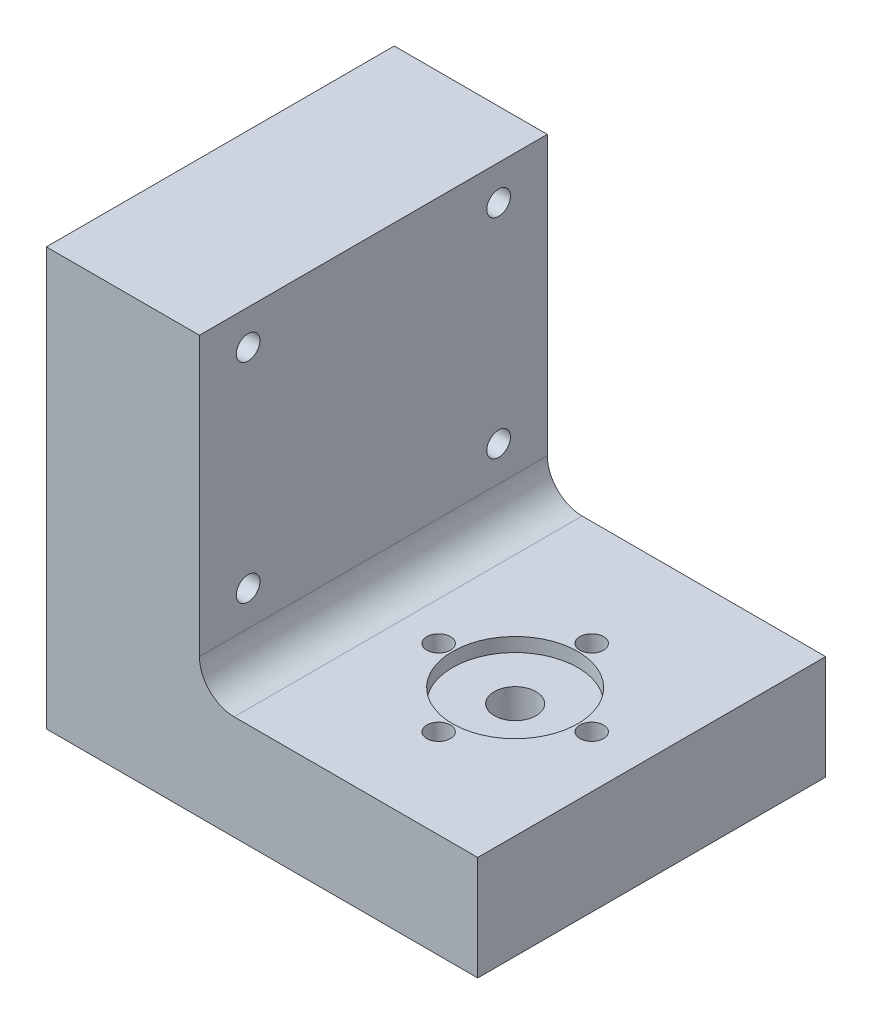
SolidWorks part; units mm, degrees
material "ABS"
ref_plane "Front Plane" through (0, 0, 0) normal (0, 0, 1) x (1, 0, 0)
ref_plane "Top Plane" through (0, 0, 0) normal (0, 1, 0) x (1, 0, 0)
ref_plane "Right Plane" through (0, 0, 0) normal (1, 0, 0) x (0, 0, -1)
sketch "Sketch1" plane through (0, 0, 0) normal (0, 0, 1) x (1, 0, 0)
  line L0 (-43.5429, 31.8) -> (-43.5429, -28.2)
  line L1 (-43.5429, -28.2) -> (18.4571, -28.2)
  line L2 (18.4571, -28.2) -> (18.4571, -13.2)
  line L3 (18.4571, -13.2) -> (-21.5429, -13.2)
  line L4 (-21.5429, -13.2) -> (-21.5429, 31.8)
  line L5 (-21.5429, 31.8) -> (-43.5429, 31.8)
  dimension "D1" = 60
  dimension "D2" = 40
  dimension "D3" = 15
  dimension "D4" = 22
extrude "Boss-Extrude1" add sketch "Sketch1" along normal blind 50
fillet "Fillet1" radius 5 1 edges at (-21.5429, -13.2, 25)
sketch "Sketch2" plane through (-21.5429, 0, 0) normal (1, 0, 0) x (0, 0, -1)
  line L0 (-50, 31.8) -> (0, 31.8) construction
  line L1 (-50, -8.2) -> (0, -8.2) construction
  line L3 (-50, -8.2) -> (-50, 31.8) construction
  line L4 (0, -8.2) -> (0, 31.8) construction
  circle A0 centre (-43, 26.8) radius 1.7
  circle A1 centre (-7, 26.8) radius 1.7
  circle A2 centre (-7, -3.2) radius 1.7
  circle A3 centre (-43, -3.2) radius 1.7
  dimension "D1" = 3.4
  dimension "D2" = 3.4
  dimension "D3" = 3.4
  dimension "D4" = 3.4
  dimension "D5" = 5
  dimension "D6" = 5
  dimension "D7" = 5
  dimension "D8" = 5
  dimension "D9" = 7
  dimension "D10" = 7
  dimension "D11" = 7
  dimension "D12" = 7
extrude "Cut-Extrude1" cut sketch "Sketch2" against normal blind 50 contours A0 | A1 | A3 | A2
sketch "Sketch3" plane through (0, -13.2, 0) normal (0, 1, 0) x (1, 0, 0)
  circle A0 centre (0, -26.1679) radius 11
  circle A1 centre (0, -26.1679) radius 3.25
  circle A2 centre (0, -26.1679) radius 9
  circle A3 centre (11, -26.1679) radius 1.7
  circle A4 centre (0, -15.1679) radius 1.7
  circle A5 centre (-11, -26.1679) radius 1.7
  circle A6 centre (0, -37.1679) radius 1.7
  dimension "D1" = 3.4
  dimension "D2" = 3.4
  dimension "D3" = 3.4
  dimension "D4" = 3.4
  dimension "D5" = 22
  dimension "D6" = 18
  dimension "D7" = 6.5
extrude "Cut-Extrude4" cut sketch "Sketch3" against normal blind 2 contours A2 A1
sketch "Sketch4" plane through (0, -13.2, 0) normal (0, 1, 0) x (1, 0, 0)
  circle A0 centre (0, -26.1679) radius 3
  dimension "D1" = 6
extrude "Cut-Extrude5" cut sketch "Sketch4" against normal blind 15
sketch "Sketch5" plane through (0, -13.2, 0) normal (0, 1, 0) x (1, 0, 0)
  circle A0 centre (0, -26.1679) radius 11
  circle A1 centre (-11, -26.1679) radius 1.7
  circle A2 centre (0, -15.1679) radius 1.7
  circle A3 centre (11, -26.1679) radius 1.7
  circle A4 centre (0, -37.1679) radius 1.7
  dimension "D1" = 22
  dimension "D2" = 3.4
  dimension "D3" = 3.4
  dimension "D4" = 3.4
  dimension "D5" = 3.4
extrude "Cut-Extrude6" cut sketch "Sketch5" against normal through all contours A2 | A1 | A4 | A3
equation "\"Bolt Circle Diameter\"= 22mm"
equation "\"h\"= 15mm"
equation "\"b\"= 50mm"
equation "\"t\"= 22mm"
equation "\"L1\"= 40mm"
equation "\"L2\"= 60mm"
equation "\"R fillet\"= 5mm"
equation "\"Shaft hole\"= 6.5mm'\""
equation "\"Bolt hole\"= 3.4mm"
equation "\"D1@Sketch1\"=\"L2\""
equation "\"D2@Sketch1\"=\"L1\""
equation "\"D3@Sketch1\"=\"h\""
equation "\"D4@Sketch1\"=\"t\""
equation "\"D1@Boss-Extrude1\"=\"b\""
equation "\"D1@Fillet1\"=\"R fillet\""
equation "\"D1@Sketch2\"=\"Bolt hole\""
equation "\"D2@Sketch2\"=\"Bolt hole\""
equation "\"D3@Sketch2\"=\"Bolt hole\""
equation "\"D4@Sketch2\"=\"Bolt hole\""
equation "\"D1@Sketch3\"=\"Bolt hole\""
equation "\"D2@Sketch3\"=\"Bolt hole\""
equation "\"D3@Sketch3\"=\"Bolt hole\""
equation "\"D4@Sketch3\"=\"Bolt hole\""
equation "\"D5@Sketch3\"=22mm"
equation "\"D6@Sketch3\"=18mm"
equation "\"D7@Sketch3\"=\"Shaft hole\""
equation "\"D1@Cut-Extrude5\"=\"h\""
